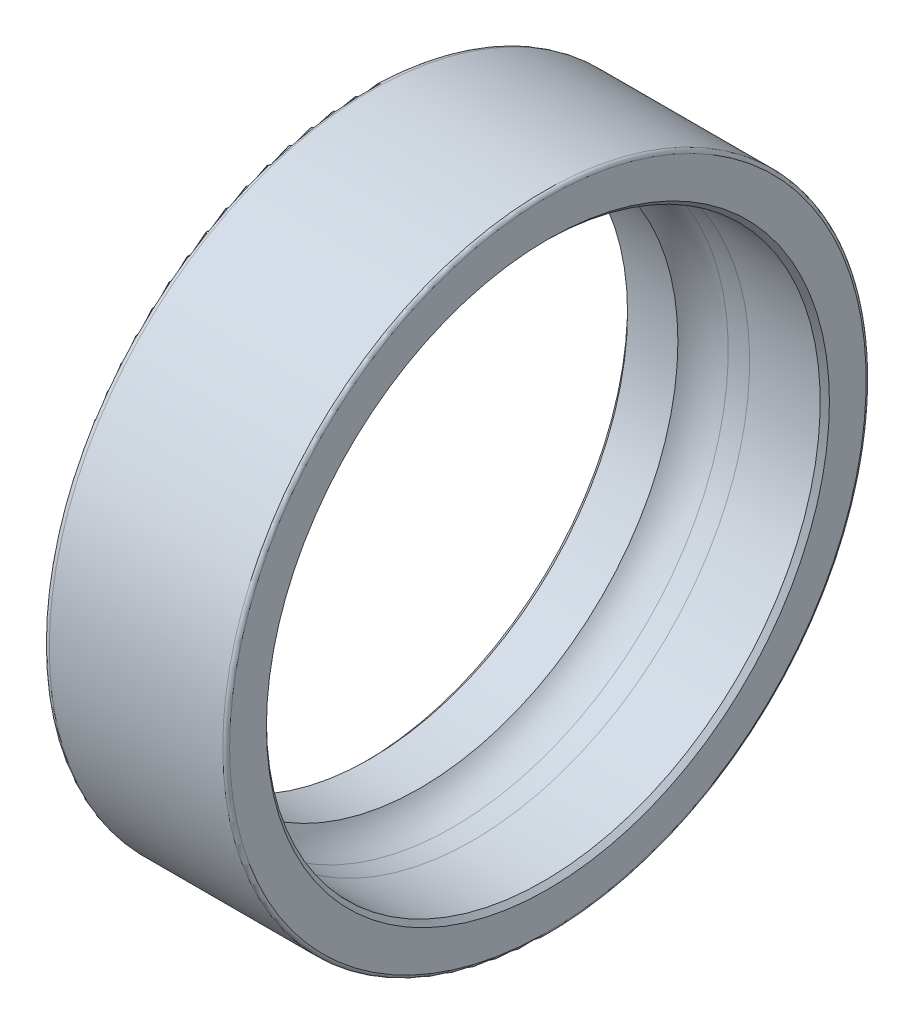
SolidWorks part; units mm, degrees
material "Chrome Stainless Steel"
ref_plane "Front Plane" through (0, 0, 0) normal (0, 0, 1) x (1, 0, 0)
ref_plane "Top Plane" through (0, 0, 0) normal (0, 1, 0) x (1, 0, 0)
ref_plane "Right Plane" through (0, 0, 0) normal (1, 0, 0) x (0, 0, -1)
ref_plane "Plane1" through (0, 0, 0) normal (0, 0, 1) x (1, 0, 0)
sketch "Sketch1" plane through (0, 0, 0) normal (0, 0, 1) x (1, 0, 0)
  line L0 (-4, 11.465) -> (-3.76, 11.225)
  line L1 (-3.76, 11.225) -> (-1.5679, 11.225)
  line L2 (-0.1412, 11.988) -> (0.7283, 12.05)
  line L3 (0.7283, 12.05) -> (3.8, 12.05)
  line L4 (3.8, 12.05) -> (4, 12.25)
  line L5 (4, 12.25) -> (4, 13.85)
  line L6 (3.85, 14) -> (-3.7, 14)
  line L7 (-4, 13.7) -> (-4, 11.465)
  line L8 (4, 0) -> (-4, 0) construction
  arc A0 (-1.5679, 11.225) -> (-0.1412, 11.988) centre (0, 10.0085) cw
  arc A1 (4, 13.85) -> (3.85, 14) centre (3.85, 13.85) ccw
  arc A2 (-3.7, 14) -> (-4, 13.7) centre (-3.7, 13.7) ccw
revolve "Revolve1" add sketch "Sketch1" angle 360 about L8
